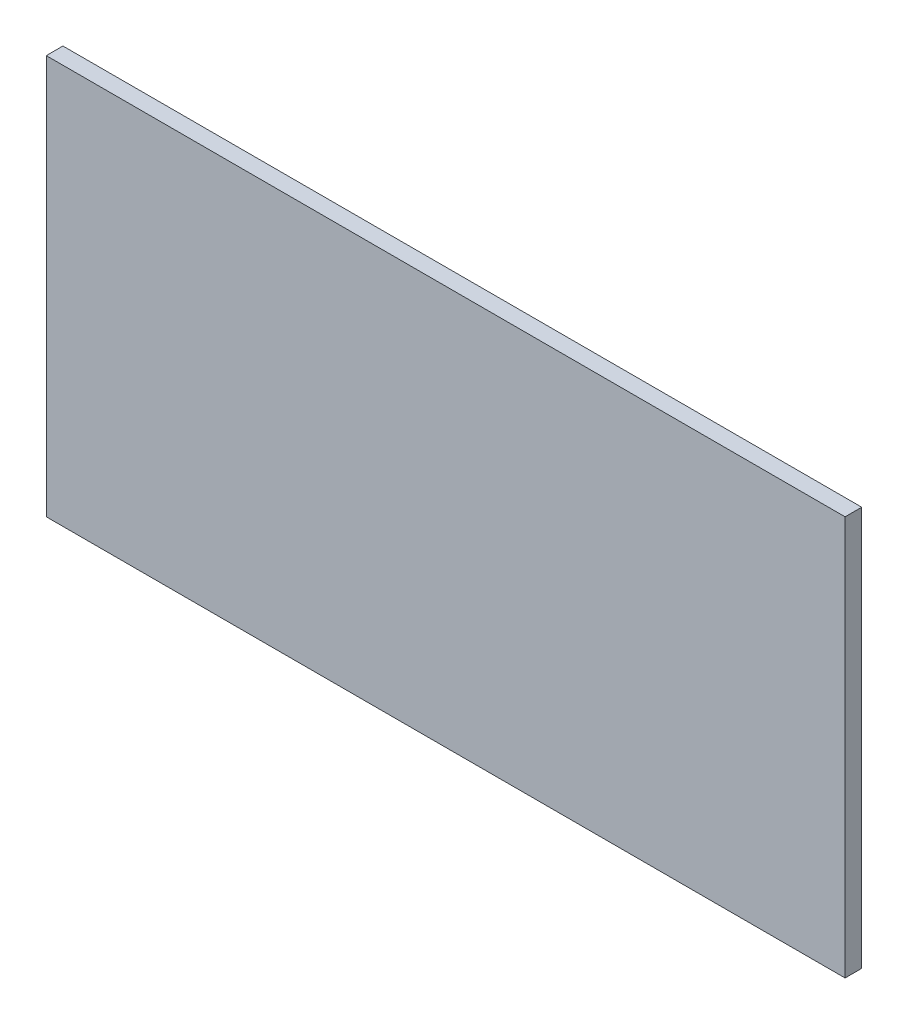
SolidWorks part; units mm, degrees
ref_plane "前视基准面" through (0, 0, 0) normal (0, 0, 1) x (1, 0, 0)
ref_plane "上视基准面" through (0, 0, 0) normal (0, 1, 0) x (1, 0, 0)
ref_plane "右视基准面" through (0, 0, 0) normal (1, 0, 0) x (0, 0, -1)
other "Configuration Table"
sketch "Sketch1" plane through (0, 0, 0) normal (0, 0, 1) x (1, 0, 0)
  line L1 (-600, -300) -> (600, -300)
  line L2 (-600, -300) -> (-600, 300)
  line L3 (-600, 300) -> (600, 300)
  line L4 (600, -300) -> (600, 300)
  line L5 (-600, -300) -> (600, 300) construction
  line L6 (-600, 300) -> (600, -300) construction
  point P0 (0, 0)
extrude "Boss-Extrude1" add sketch "Sketch1" against normal blind 25
ref_plane "bottom_face_ref" through (0, 0, -25) normal (0, 0, 1) x (1, 0, 0)
ref_plane "top_face_ref" through (0, 0, 0) normal (0, 0, 1) x (1, 0, 0)
